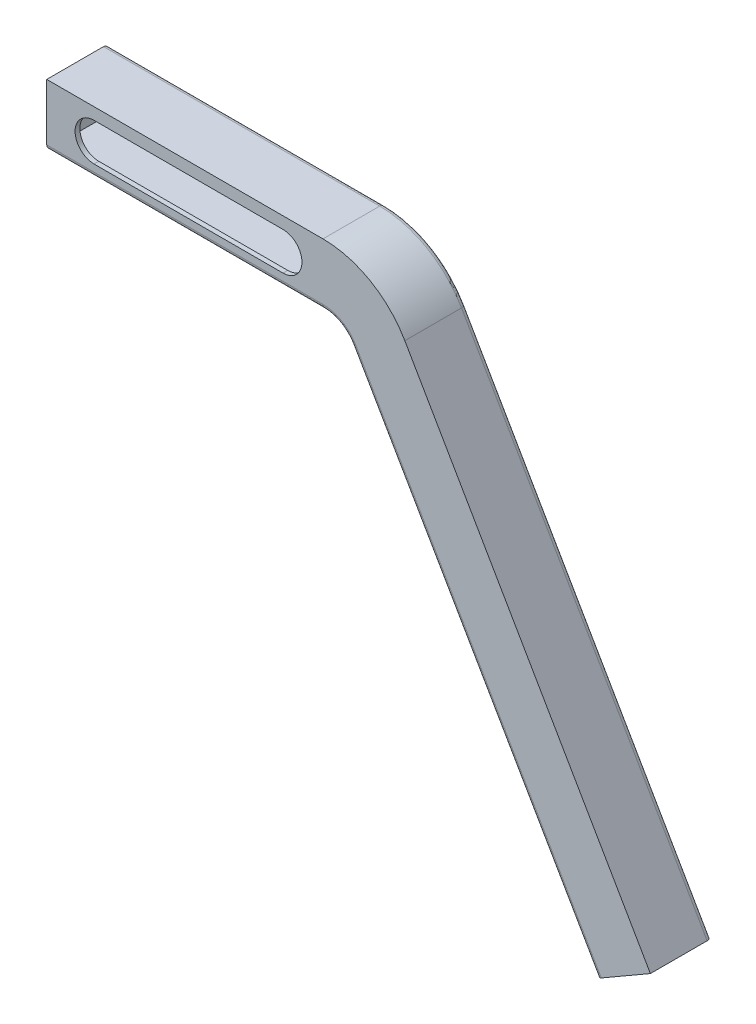
SolidWorks part; units mm, degrees
material "Plain Carbon Steel"
ref_plane "Front Plane" through (0, 0, 0) normal (0, 0, 1) x (1, 0, 0)
ref_plane "Top Plane" through (0, 0, 0) normal (0, 1, 0) x (1, 0, 0)
ref_plane "Right Plane" through (0, 0, 0) normal (1, 0, 0) x (0, 0, -1)
sketch "Sketch1" plane through (0, 0, 0) normal (0, 0, 1) x (1, 0, 0)
  line L0 (-172.047, 25.4) -> (-23.5764, 25.4)
  line L1 (20.4177, 0) -> (152.4, -228.6)
  line L2 (-172.047, -7.62) -> (-23.5764, -7.62)
  line L3 (-8.1784, -16.51) -> (123.8038, -245.11)
  line L4 (-172.047, 25.4) -> (-172.047, -7.62)
  line L5 (123.8038, -245.11) -> (152.4, -228.6)
  arc A0 (-23.5764, 25.4) -> (20.4177, 0) centre (-23.5764, -25.4) cw
  arc A1 (-23.5764, -7.62) -> (-8.1784, -16.51) centre (-23.5764, -25.4) cw
  point P6 (5.753, 25.4)
  dimension "D6" = 50.8
  dimension "D1" = 120
  dimension "D2" = 177.8
  dimension "D3" = 254
  dimension "D4" = 25.4
  dimension "D5" = 152.4
  dimension "D7" = 33.02
extrude "Boss-Extrude1" add sketch "Sketch1" along normal blind 33.02
shell "Shell1" thickness 2.54
sketch "Sketch2" plane through (137.0867, -237.4411, 0) normal (0.5, -0.866, 0) x (0.866, 0.5, 0)
  line L0 (17.6823, 33.02) -> (17.6823, 0) construction
  line L1 (-12.7977, 2.54) -> (15.1423, 2.54)
  line L2 (-12.7977, 2.54) -> (-12.7977, 30.48)
  line L3 (-12.7977, 30.48) -> (15.1423, 30.48)
  line L4 (15.1423, 2.54) -> (15.1423, 30.48)
  line L5 (-12.7977, 2.54) -> (15.1423, 30.48) construction
  line L6 (-12.7977, 30.48) -> (15.1423, 2.54) construction
  line L7 (-15.3377, 33.02) -> (-15.3377, 0) construction
  line L8 (-15.3377, 33.02) -> (17.6823, 33.02) construction
  line L9 (-15.3377, 0) -> (17.6823, 0) construction
  point P0 (1.1723, 16.51)
  dimension "D1" = 2.54
  dimension "D2" = 2.54
  dimension "D3" = 2.54
  dimension "D4" = 2.54
extrude "Cut-Extrude1" cut sketch "Sketch2" against normal up to next
sketch "Sketch3" plane through (0, 0, 33.02) normal (0, 0, 1) x (1, 0, 0)
  line L0 (-172.047, 25.4) -> (-172.047, -7.62) construction
  line L1 (-146.647, 19.05) -> (-45.047, 19.05)
  line L2 (-146.647, -1.27) -> (-50.127, -1.27)
  line L7 (-50.127, -1.27) -> (-45.047, -1.27)
  line L8 (-172.047, -7.62) -> (-23.5764, -7.62) construction
  arc A0 (-146.647, 19.05) -> (-146.647, -1.27) centre (-146.647, 8.89) ccw
  arc A1 (-45.047, -1.27) -> (-45.047, 19.05) centre (-45.047, 8.89) ccw
  dimension "D1" = 10.16
  dimension "D2" = 25.4
  dimension "D4" = 127
  dimension "D5" = 16.51
  dimension "D3" = 121.92
extrude "Cut-Extrude2" cut sketch "Sketch3" against normal blind 2.54
sketch "Sketch4" plane through (0, 0, 0) normal (0, 0, -1) x (-1, 0, 0)
  line L2 (45.047, -1.27) -> (146.647, -1.27)
  line L3 (146.647, 19.05) -> (45.047, 19.05)
  line L4 (45.047, -1.27) -> (146.647, -1.27)
  line L5 (146.647, 19.05) -> (45.047, 19.05)
  arc A2 (146.647, -1.27) -> (146.647, 19.05) centre (146.647, 8.89) ccw
  arc A3 (45.047, 19.05) -> (45.047, -1.27) centre (45.047, 8.89) ccw
  arc A4 (146.647, -1.27) -> (146.647, 19.05) centre (146.647, 8.89) ccw
  arc A5 (45.047, 19.05) -> (45.047, -1.27) centre (45.047, 8.89) ccw
  dimension "D1" = 0
extrude "Cut-Extrude3" cut sketch "Sketch4" against normal up to next
ref_plane "Plane1" through (152.4, -228.6, 0) normal (-0.5, 0.866, 0) x (0.866, 0.5, 0)
sketch "Sketch6" plane through (0, 0, 0) normal (0, 0, -1) x (-1, 0, 0)
  circle A0 centre (-116.5119, -199.46) radius 6.35 construction
  circle A1 centre (-107.6219, -184.0621) radius 6.35 construction
  circle A2 centre (-98.7319, -168.6642) radius 6.35 construction
  circle A3 centre (-89.8419, -153.2662) radius 6.35 construction
  circle A4 centre (-116.5119, -199.46) radius 6.35
  circle A5 centre (-107.6219, -184.0621) radius 6.35
  circle A6 centre (-98.7319, -168.6642) radius 6.35
  circle A7 centre (-89.8419, -153.2662) radius 6.35
extrude "Cut-Extrude4" cut sketch "Sketch6" against normal up to next
sketch "Sketch7" plane through (0, 0, 0) normal (0, 0, -1) x (-1, 0, 0)
  circle A0 centre (-125.4019, -214.858) radius 6.35
  dimension "D1" = 12.7
extrude "Cut-Extrude5" cut sketch "Sketch7" against normal up to next
sketch "Sketch8" plane through (-172.047, 0, 0) normal (-1, 0, 0) x (0, 0, 1)
  line L1 (2.54, 22.86) -> (30.48, 22.86)
  line L2 (2.54, 22.86) -> (2.54, -5.08)
  line L3 (2.54, -5.08) -> (30.48, -5.08)
  line L4 (30.48, 22.86) -> (30.48, -5.08)
extrude "Boss-Extrude2" add sketch "Sketch8" against normal blind 2.54
fillet "Fillet1" radius 2.54 12 edges at (57.8127, -130.81, 0) (-14.6864, -10.0021, 0) (57.8127, -130.81, 33.02) (-14.6864, -10.0021, 33.02) (86.4089, -114.3, 0) (1.8236, 18.5941, 0) (84.2092, -115.57, 30.48) (0.5536, 16.3944, 30.48) (-97.8117, -7.62, 0) (-97.8117, -7.62, 33.02) (-97.8117, 25.4, 0) (-96.5417, 22.86, 30.48)
